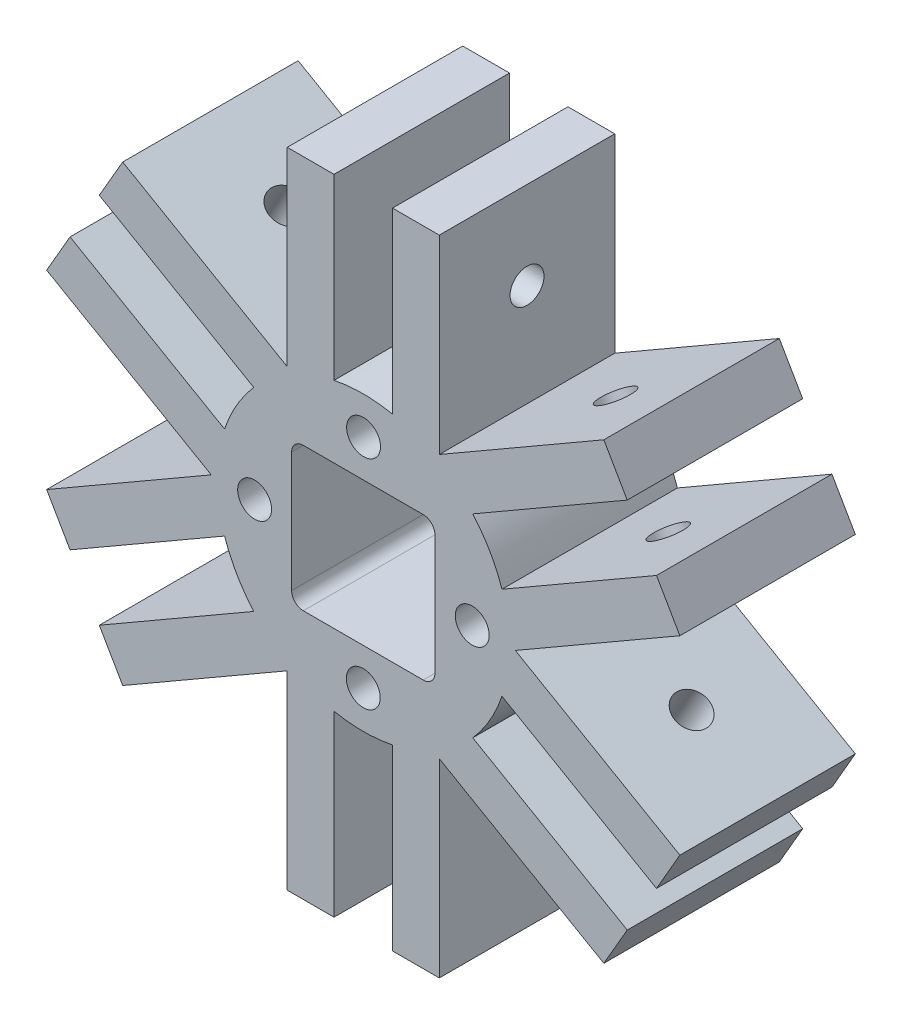
SolidWorks part; units mm, degrees
ref_plane "Front Plane" through (0, 0, 0) normal (0, 0, 1) x (1, 0, 0)
ref_plane "Top Plane" through (0, 0, 0) normal (0, 1, 0) x (1, 0, 0)
ref_plane "Right Plane" through (0, 0, 0) normal (1, 0, 0) x (0, 0, -1)
sketch "Sketch1" plane through (0, 0, 0) normal (0, 0, 1) x (1, 0, 0)
  circle A0 centre (0, 0) radius 12.5
  dimension "D2" = 25
extrude "Boss-Extrude1" add sketch "Sketch1" along normal mid plane 15
sketch "Sketch4" plane through (0, 0, 7.5) normal (0, 0, 1) x (1, 0, 0)
  line L0 (29.7723, 0) -> (-29.7723, 0) construction
  line L2 (-6.5, 0) -> (-2.5, 0)
  line L3 (0, 0) -> (0, 15.8331) construction
  line L4 (-6.5, 0) -> (-6.5, 27.5)
  line L5 (-6.5, 27.5) -> (-2.5, 27.5)
  line L6 (-2.5, 0) -> (-2.5, 27.5)
  line L7 (0, -30.25) -> (0, 30.25) construction
  line L8 (6.5, 27.5) -> (2.5, 27.5)
  line L9 (2.5, 0) -> (2.5, 27.5)
  line L10 (6.5, 0) -> (2.5, 0)
  line L11 (6.5, 0) -> (6.5, 27.5)
  dimension "D1" = 27.5
  dimension "D3" = 2.5
  dimension "D2" = 4
extrude "Boss-Extrude3" add sketch "Sketch4" against normal up to surface (15 mm away) up to face at (12.5, 0, -7.5)
pattern_circular "CirPattern7" count 6 over 360 about axis through (0, 0, 0) along (0, 0, 1) of "Boss-Extrude3"
sketch "Sketch7" plane through (-6.5, 0, 0) normal (-1, 0, 0) x (0, 0, 1)
  line L0 (-7.5, 27.5) -> (7.5, 27.5) construction
  line L1 (-7.5, 11.2583) -> (-7.5, 27.5) construction
  circle A0 centre (0, 20) radius 1.45
  circle A1 centre (40, 20) radius 1.45
  circle A2 centre (80, 20) radius 1.45
  circle A3 centre (120, 20) radius 1.45
  circle A4 centre (160, 20) radius 1.45
  dimension "D1" = 2.9
  dimension "D2" = 7.5
  dimension "D3" = 7.5
  dimension "D4" = 5
extrude "Cut-Extrude2" cut sketch "Sketch7" against normal blind 17
pattern_circular "CirPattern9" count 6 over 360 of "Cut-Extrude2"
sketch "Sketch8" plane through (0, 0, 7.5) normal (0, 0, 1) x (1, 0, 0)
  line L2 (-6.125, 6.125) -> (6.125, 6.125)
  line L3 (-6.125, 6.125) -> (-6.125, -6.125)
  line L4 (-6.125, -6.125) -> (6.125, -6.125)
  line L5 (6.125, 6.125) -> (6.125, -6.125)
  line L6 (-6.125, 6.125) -> (6.125, -6.125) construction
  line L7 (-6.125, -6.125) -> (6.125, 6.125) construction
  point P5 (0, 0)
  point P14 (0, 0)
  dimension "D1" = 12.25
extrude "Cut-Extrude3" cut sketch "Sketch8" against normal up to next
sketch "Sketch9" plane through (0, 0, 7.5) normal (0, 0, 1) x (1, 0, 0)
  line L0 (29.7723, 0) -> (-29.7723, 0) construction
  line L1 (6.125, -6.125) -> (6.125, 6.125) construction
  circle A0 centre (9.3125, 0) radius 1.45
  circle A1 centre (0, -9.2875) radius 1.45
  circle A2 centre (-9.2875, 0.025) radius 1.45
  circle A3 centre (0.025, 9.3125) radius 1.45
  point P14 (0.0125, 0.0125)
  dimension "D1" = 2.9
  dimension "D2" = 3.1875
  dimension "D3" = 4
extrude "Cut-Extrude4" cut sketch "Sketch9" against normal blind 10
fillet "Fillet1" radius 1 4 edges at (-6.125, 6.125, 0) (6.125, 6.125, 0) (6.125, -6.125, 0) (-6.125, -6.125, 0)
equation "\"drumDiameter\"= 25"
equation "\"D2@Sketch1\"=\"drumDiameter\""
equation "\"drumLength\" = 15"
equation "\"D1@Sketch4\"=\"drumDiameter\"*(0.5+\"drumAbove\")"
equation "\"foamThickness\"= 5"
equation "\"D3@Sketch4\"=\"foamThickness\"/2"
equation "\"drumAbove\"= 0.6"
equation "\"D2@Sketch7\"=\"drumDiameter\"*\"drumAbove\"/2"
equation "\"holderThicc\"= 4"
equation "\"D2@Sketch4\"=\"holderThicc\""
equation "\"D1@Boss-Extrude1\"=\"drumLength\""
equation "\"squareBarLength\"= 12.25"
equation "\"D1@Sketch8\"=\"squareBarLength\""
equation "\"D2@Sketch9\"=(\"drumDiameter\"/2-\"squareBarLength\"/2)/2"
